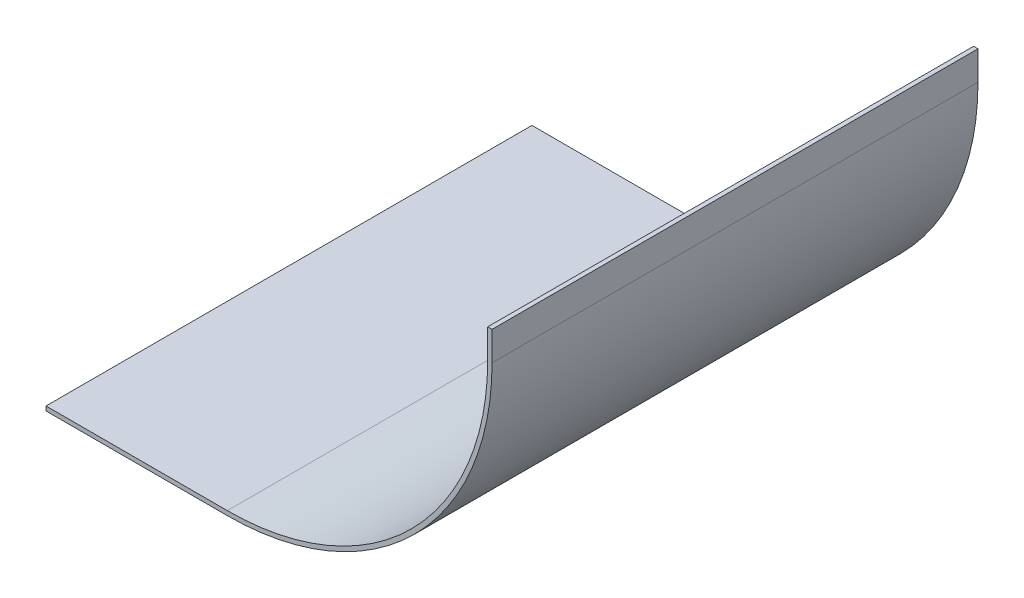
SolidWorks part; units mm, degrees
ref_plane "Front Plane" through (0, 0, 0) normal (0, 0, 1) x (1, 0, 0)
ref_plane "Top Plane" through (0, 0, 0) normal (0, 1, 0) x (1, 0, 0)
ref_plane "Right Plane" through (0, 0, 0) normal (1, 0, 0) x (0, 0, -1)
sketch "Sketch1" plane through (0, 0, 0) normal (0, 0, 1) x (1, 0, 0)
  line L0 (1200, -4815) -> (950, -4815)
  line L1 (1200, -4815) -> (700, -4815) construction
  line L2 (1565, -4410) -> (1565, -4450)
  arc A1 (1200, -4815) -> (1565, -4450) centre (1200, -4450) ccw construction
  arc A2 (1200, -4815) -> (1565, -4450) centre (1200, -4450) ccw
extrude "Extrude-Thin1" add sketch "Sketch1" against normal up to vertex (670 mm away) thin
